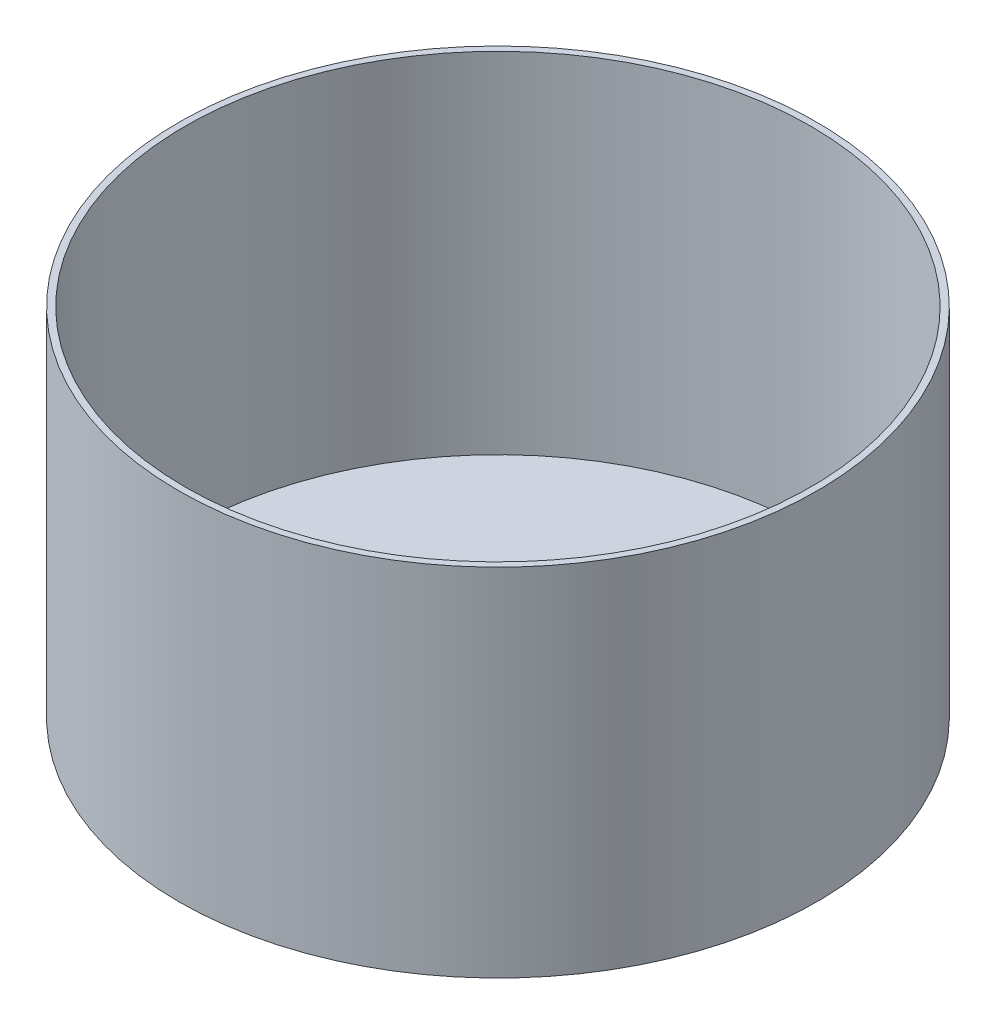
SolidWorks part; units mm, degrees
ref_plane "Front Plane" through (0, 0, 0) normal (0, 0, 1) x (1, 0, 0)
ref_plane "Top Plane" through (0, 0, 0) normal (0, 1, 0) x (1, 0, 0)
ref_plane "Right Plane" through (0, 0, 0) normal (1, 0, 0) x (0, 0, -1)
sketch "Basket Base Ring Sketch" plane through (0, 0, 0) normal (0, 1, 0) x (1, 0, 0)
  circle A0 centre (0, 0) radius 148
  circle A1 centre (0, 0) radius 65
  dimension "D1" = 296
  dimension "D2" = 130
extrude "Basket Base Ring" add sketch "Basket Base Ring Sketch" along normal blind 3
sketch "Basket Wall Sketch" plane through (0, 0, 0) normal (0, 1, 0) x (1, 0, 0)
  circle A0 centre (0, 0) radius 148
  circle A1 centre (0, 0) radius 145
  dimension "D1" = 296
  dimension "D2" = 290
extrude "Basket Wall" add sketch "Basket Wall Sketch" along normal blind 165
